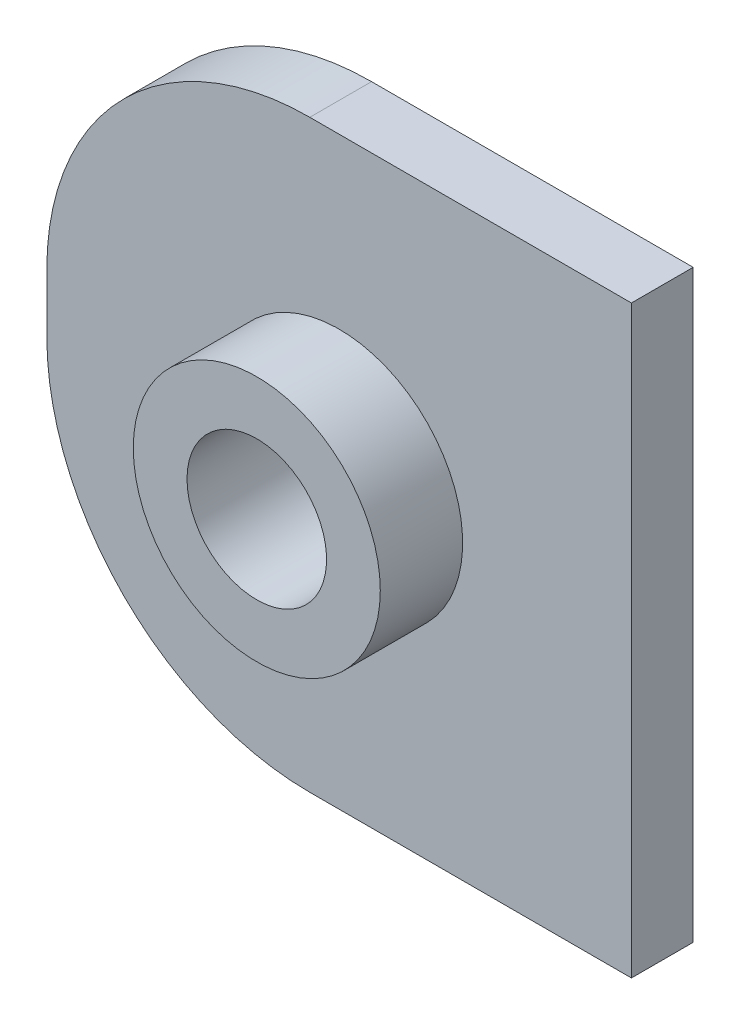
SolidWorks part; units mm, degrees
ref_plane "Front Plane" through (0, 0, 0) normal (0, 0, 1) x (1, 0, 0)
ref_plane "Top Plane" through (0, 0, 0) normal (0, 1, 0) x (1, 0, 0)
ref_plane "Right Plane" through (0, 0, 0) normal (1, 0, 0) x (0, 0, -1)
sketch "Sketch1" plane through (0, 0, 0) normal (0, 0, 1) x (1, 0, 0)
  line L1 (-9.017, -9.017) -> (9.017, -9.017)
  line L2 (-9.017, -9.017) -> (-9.017, 9.017)
  line L3 (-9.017, 9.017) -> (9.017, 9.017)
  line L4 (9.017, -9.017) -> (9.017, 9.017)
  line L5 (-9.017, -9.017) -> (9.017, 9.017) construction
  line L6 (-9.017, 9.017) -> (9.017, -9.017) construction
  circle A0 centre (0, 0) radius 2.1526
  dimension "D2" = 4.3053
  dimension "D1" = 18.034
extrude "Boss-Extrude1" add sketch "Sketch1" along normal blind 1.905
sketch "Sketch2" plane through (0, 0, 1.905) normal (0, 0, 1) x (1, 0, 0)
  circle A0 centre (0, 0) radius 3.81
  circle A1 centre (0, 0) radius 2.1526 construction
  circle A2 centre (0, 0) radius 2.1526
  dimension "D1" = 7.62
extrude "Boss-Extrude2" add sketch "Sketch2" along normal blind 2.54
sketch "Sketch3" plane through (0, 0, 0) normal (0, 0, -1) x (-1, 0, 0)
  line L0 (-9.017, 9.017) -> (9.017, 9.017) construction
  line L1 (9.017, 9.017) -> (9.017, -9.017) construction
  line L2 (9.017, 0.9045) -> (9.017, 9.017)
  line L3 (9.017, 9.017) -> (0.9045, 9.017)
  line L4 (0, 0) -> (1.5222, 1.5222) construction
  line L5 (-0.1266, 0) -> (-50000.1266, 0) construction
  line L6 (9.017, -9.017) -> (0.9045, -9.017)
  line L7 (9.017, -0.9045) -> (9.017, -9.017)
  arc A0 (0.9045, 9.017) -> (9.017, 0.9045) centre (0.9045, 0.9045) cw
  circle A1 centre (0, 0) radius 2.1526 construction
  arc A2 (0.9045, -9.017) -> (9.017, -0.9045) centre (0.9045, -0.9045) ccw
  point P9 (6.6409, 6.6409)
  point P10 (1.5222, 1.5222)
  point P21 (6.6409, -6.6409)
  dimension "D1" = 7.239
extrude "Cut-Extrude1" cut sketch "Sketch3" against normal through all
